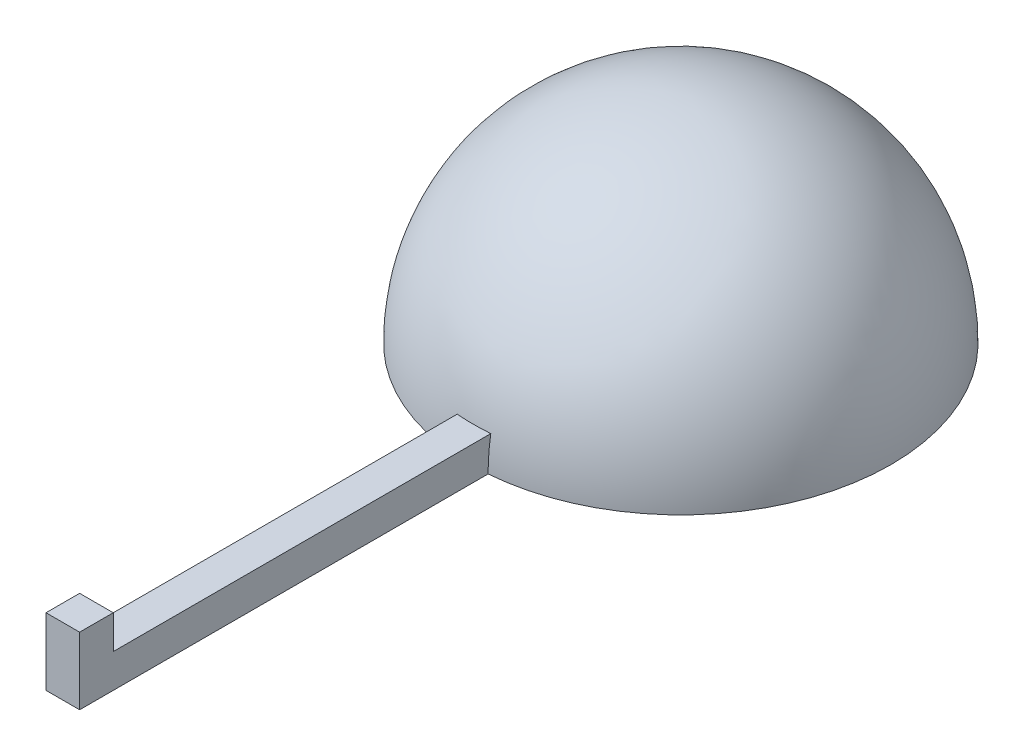
SolidWorks part; units mm, degrees
ref_plane "Front Plane" through (0, 0, 0) normal (0, 0, 1) x (1, 0, 0)
ref_plane "Top Plane" through (0, 0, 0) normal (0, 1, 0) x (1, 0, 0)
ref_plane "Right Plane" through (0, 0, 0) normal (1, 0, 0) x (0, 0, -1)
sketch "Sketch1" plane through (0, 0, 0) normal (0, 1, 0) x (1, 0, 0)
  line L0 (-50, 0) -> (50, 0)
  arc A0 (-50, 0) -> (50, 0) centre (0, 0) cw
  dimension "D1" = 50
revolve "Revolve1" add sketch "Sketch1" angle 180 about L0
shell "Shell3" thickness 3
sketch "Sketch5" plane through (0, 0, 0) normal (1, 0, 0) x (0, 0, -1)
  line L0 (-47, 0) -> (-47, 8)
  line L1 (-47, 8) -> (-139, 8)
  line L2 (-139, 8) -> (-139, 16)
  line L3 (-139, 16) -> (-147, 16)
  line L4 (-147, 16) -> (-147, 0)
  line L5 (-147, 0) -> (-47, 0)
  dimension "D1" = 100
  dimension "D2" = 8
  dimension "D3" = 8
  dimension "D4" = 8
extrude "Boss-Extrude1" add sketch "Sketch5" along normal mid plane 8
equation "\"D4@Sketch5\"=\"D2@Sketch5\""
equation "\"D3@Sketch5\"=\"D2@Sketch5\""
